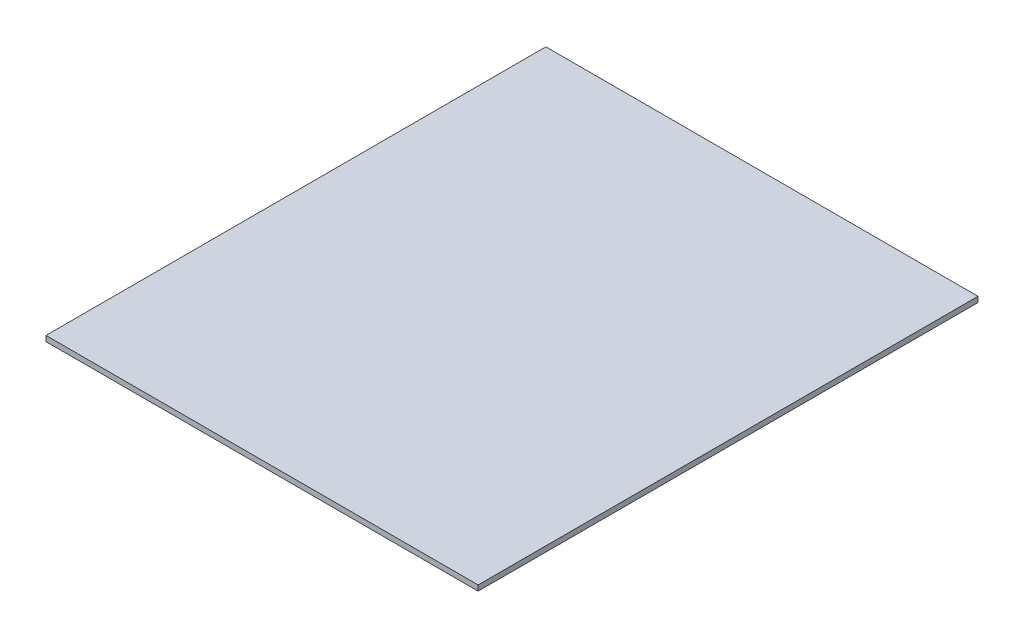
SolidWorks part; units mm, degrees
ref_plane "Front Plane" through (0, 0, 0) normal (0, 0, 1) x (1, 0, 0)
ref_plane "Top Plane" through (0, 0, 0) normal (0, 1, 0) x (1, 0, 0)
ref_plane "Right Plane" through (0, 0, 0) normal (1, 0, 0) x (0, 0, -1)
sketch "Sketch1" plane through (0, 0, 0) normal (0, 1, 0) x (1, 0, 0)
  line L1 (-253.2063, -292.8938) -> (253.2062, -292.8938)
  line L2 (-253.2063, -292.8938) -> (-253.2063, 292.8938)
  line L3 (-253.2063, 292.8938) -> (253.2062, 292.8938)
  line L4 (253.2062, -292.8938) -> (253.2062, 292.8938)
  line L5 (-253.2063, -292.8938) -> (253.2062, 292.8938) construction
  line L6 (-253.2063, 292.8938) -> (253.2062, -292.8938) construction
  point P0 (0, 0)
  dimension "D1" = 506.4125
  dimension "D2" = 585.7875
extrude "Boss-Extrude1" add sketch "Sketch1" along normal blind 6.35
